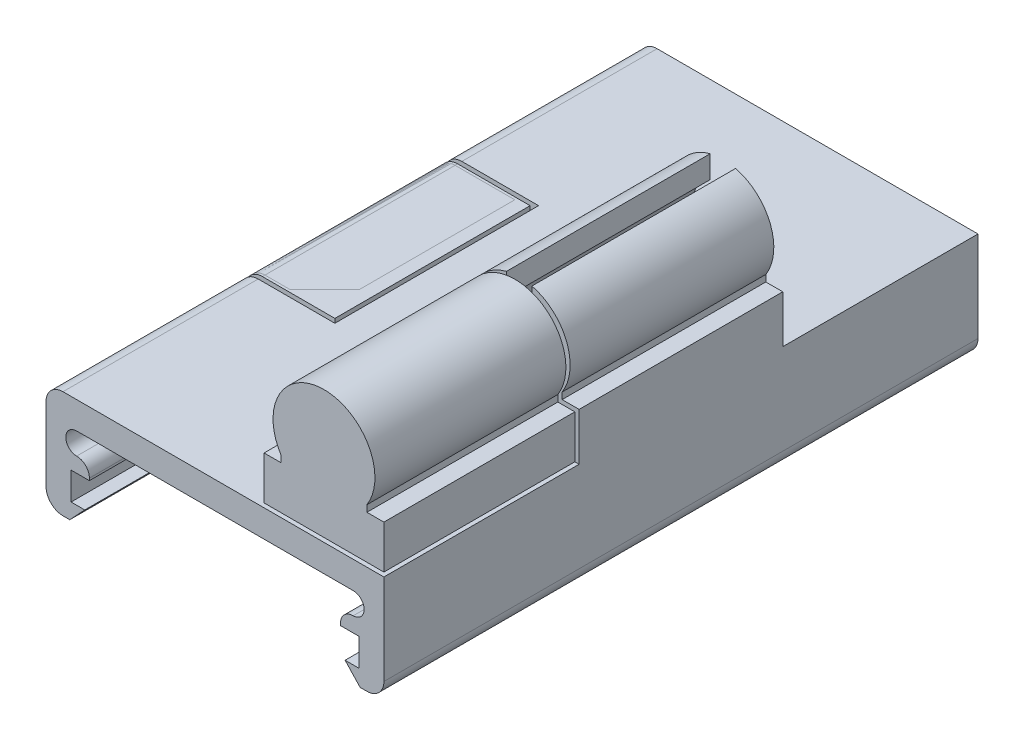
SolidWorks part; units mm, degrees
ref_plane "Front Plane" through (0, 0, 0) normal (0, 0, 1) x (1, 0, 0)
ref_plane "Top Plane" through (0, 0, 0) normal (0, 1, 0) x (1, 0, 0)
ref_plane "Right Plane" through (0, 0, 0) normal (1, 0, 0) x (0, 0, -1)
sketch "Sketch1" plane through (0, 0, 0) normal (0, 0, 1) x (1, 0, 0)
  line L0 (-10, 0.77) -> (7, 0.77) construction
  line L1 (-10, 0.77) -> (-9.1935, 0.77)
  line L2 (-9.1935, 0.77) -> (-10.0783, -0.1732)
  line L3 (-10.0783, -0.1732) -> (-10.478, -0.1732)
  line L4 (-11.478, 0.8268) -> (-11.478, 5.16)
  line L5 (-10.478, 6.16) -> (7.4264, 6.16)
  line L6 (-10, 0.77) -> (-10, 2.4)
  line L7 (-10, 2.4) -> (-8.9215, 2.4)
  line L8 (-8.9215, 2.4) -> (-8.9215, 2.5276)
  line L11 (-9.6715, 4.56) -> (6.6199, 4.56)
  line L12 (-1.5258, -9.4347) -> (-1.5258, -0.4273) construction
  line L13 (-1.5258, 6.16) -> (-1.5258, 4.56) construction
  line L14 (-10, 0.77) -> (-10, 2.4) construction
  line L17 (5.8699, 2.4) -> (5.8699, 2.5276)
  line L18 (6.9484, 2.4) -> (5.8699, 2.4)
  line L19 (6.9484, 0.77) -> (6.9484, 2.4)
  line L20 (8.4264, 0.8268) -> (8.4264, 5.16)
  line L21 (7.0267, -0.1732) -> (7.4264, -0.1732)
  line L22 (6.1419, 0.77) -> (7.0267, -0.1732)
  line L23 (6.9484, 0.77) -> (6.1419, 0.77)
  line L24 (8.4264, 5.16) -> (8.4264, 6.16)
  line L25 (8.4264, 6.16) -> (7.4264, 6.16)
  line L26 (7, 0.77) -> (-10, 0.77) construction
  line L27 (-10, 2.4) -> (7, 2.4) construction
  line L28 (-10, 0.77) -> (7, 0.77) construction
  line L30 (0.73, -0.84) -> (3.37, -0.84) construction
  arc A0 (-10.478, -0.1732) -> (-11.478, 0.8268) centre (-10.478, 0.8268) cw
  arc A1 (-11.478, 5.16) -> (-10.478, 6.16) centre (-10.478, 5.16) cw
  arc A4 (-8.9215, 2.5276) -> (-9.6715, 3.2776) centre (-9.6715, 2.5276) ccw
  arc A5 (5.8699, 2.5276) -> (6.6199, 3.2776) centre (6.6199, 2.5276) cw
  arc A9 (7.4264, -0.1732) -> (8.4264, 0.8268) centre (7.4264, 0.8268) ccw
  arc A12 (-9.6715, 4.56) -> (-9.6715, 3.2776) centre (-9.6715, 3.9188) ccw
  arc A13 (6.6199, 4.56) -> (6.6199, 3.2776) centre (6.6199, 3.9188) cw
  point P48 (6.9742, 3.7616)
  dimension "D2" = 1
  dimension "D8" = 0.75
  dimension "D1" = 0
  dimension "D3" = 7
  dimension "D4" = 1.6
extrude "Boss-Extrude1" add sketch "Sketch1" against normal up to surface (35 mm away)
ref_plane "Plane4" through (0, 0, -17.5) normal (0, 0, 1) x (1, 0, 0)
sketch "Sketch2" plane through (0, 0, -17.5) normal (0, 0, -1) x (-1, 0, 0)
  line L0 (-8.4264, 6.16) -> (10.478, 6.16) construction
  line L1 (-7.4264, 6.16) -> (-2.3705, 6.16)
  line L2 (-2.3705, 9.3446) -> (-2.3705, 6.16)
  line L3 (-7.4264, 9.3446) -> (-7.4264, 6.16)
  line L4 (-8.4264, 0.8268) -> (-8.4264, 6.16) construction
  arc A1 (-2.3705, 9.3446) -> (-7.4264, 9.3446) centre (-4.8984, 10.96) ccw
  circle A2 centre (-4.8984, 10.96) radius 1.75
  dimension "D1" = 3.5
  dimension "D2" = 3
  dimension "D3" = 4.8
  dimension "D4" = 2.528
  dimension "D5" = 1
extrude "Boss-Extrude2" add sketch "Sketch2" along normal mid plane 12
sketch "Sketch3" plane through (0, 6.16, 0) normal (0, 1, 0) x (1, 0, 0)
  line L0 (-7.46, 11.0606) -> (-7.46, 34.5606) construction
  line L1 (-5.96, 23.5) -> (-12.7878, 23.5)
  line L2 (-5.96, 23.5) -> (-5.96, 11.5)
  line L3 (-5.96, 11.5) -> (-12.7878, 11.5)
  line L4 (-12.7878, 23.5) -> (-12.7878, 11.5)
  line L5 (-7.46, 22.5) -> (-10, 22.5) construction
  line L6 (-10, 12.5) -> (-7.46, 12.5) construction
  line L7 (-6.8246, 22.5) -> (-9.3646, 22.5) construction
  line L8 (-9.3646, 12.5) -> (-6.8246, 12.5) construction
  dimension "D1" = 1.5
  dimension "D2" = 1
  dimension "D3" = 1
  dimension "D4" = 1
  dimension "D5" = 6.8278
  dimension "D6" = 1
extrude "Cut-Extrude1" cut sketch "Sketch3" against normal through all
sketch "Sketch4" plane through (0, 0, 0) normal (0, 0, 1) x (1, 0, 0)
  line L0 (8.4264, 6.16) -> (-10.478, 6.16) construction
  line L3 (2.3705, 6.16) -> (7.4264, 6.16)
  line L4 (7.4264, 6.16) -> (7.4264, 9.3446)
  line L5 (2.3705, 9.3446) -> (2.3705, 6.16)
  line L7 (7.4264, 6.41) -> (7.4264, 9.3446)
  line L8 (2.3705, 9.3446) -> (2.3705, 6.41)
  line L9 (2.3705, 6.41) -> (7.4264, 6.41)
  arc A5 (7.4264, 9.3446) -> (2.3705, 9.3446) centre (4.8984, 10.96) ccw
  arc A8 (7.4264, 9.3446) -> (2.3705, 9.3446) centre (4.8984, 10.96) ccw
  dimension "D2" = 0.25
  dimension "D1" = 0
extrude "Boss-Extrude9" add sketch "Sketch4" against normal offset from surface (11.25 mm away) 0.25 separate body up to face at (4.8984, 8.9062, -11.5)
sketch "Sketch6" plane through (0, 0, -23.5) normal (0, 0, 1) x (1, 0, 0)
  line L0 (-6.96, 6.16) -> (-6.96, 4.56)
  line L1 (-5.96, 4.56) -> (-5.96, 6.16) construction
  line L12 (-11.478, 5.16) -> (-11.478, 0.8268)
  line L13 (-10.478, -0.1732) -> (-10.0783, -0.1732)
  line L14 (-10.0783, -0.1732) -> (-9.1935, 0.77)
  line L15 (-9.1935, 0.77) -> (-10, 0.77)
  line L16 (-10, 0.77) -> (-10, 2.4)
  line L17 (-10, 2.4) -> (-8.9215, 2.4)
  line L18 (-8.9215, 2.4) -> (-8.9215, 2.5276)
  line L21 (-9.6715, 4.56) -> (-5.96, 4.56)
  line L22 (-5.96, 4.56) -> (-5.96, 6.16)
  line L23 (-5.96, 6.16) -> (-10.478, 6.16)
  line L24 (-11.478, 5.16) -> (-11.478, 0.8268)
  line L25 (-10.478, -0.1732) -> (-10.0783, -0.1732)
  line L26 (-10.0783, -0.1732) -> (-9.1935, 0.77)
  line L27 (-9.1935, 0.77) -> (-10, 0.77)
  line L28 (-10, 0.77) -> (-10, 2.4)
  line L29 (-10, 2.4) -> (-8.9215, 2.4)
  line L30 (-8.9215, 2.4) -> (-8.9215, 2.5276)
  line L33 (-9.6715, 4.56) -> (-6.96, 4.56)
  line L35 (-6.96, 6.16) -> (-10.478, 6.16)
  arc A4 (-9.6715, 4.56) -> (-9.6715, 3.2776) centre (-9.6715, 3.9188) ccw
  arc A5 (-10.478, 6.16) -> (-11.478, 5.16) centre (-10.478, 5.16) ccw
  arc A6 (-11.478, 0.8268) -> (-10.478, -0.1732) centre (-10.478, 0.8268) ccw
  arc A7 (-8.9215, 2.5276) -> (-9.6715, 3.2776) centre (-9.6715, 2.5276) ccw
  arc A9 (-9.6715, 4.56) -> (-9.6715, 3.2776) centre (-9.6715, 3.9188) ccw
  arc A10 (-10.478, 6.16) -> (-11.478, 5.16) centre (-10.478, 5.16) ccw
  arc A11 (-11.478, 0.8268) -> (-10.478, -0.1732) centre (-10.478, 0.8268) ccw
  arc A12 (-8.9215, 2.5276) -> (-9.6715, 3.2776) centre (-9.6715, 2.5276) ccw
  dimension "D2" = 1
  dimension "D1" = 0
extrude "Boss-Extrude5" add sketch "Sketch6" along normal offset from surface (11.2 mm away) 0.4 from offset 0.4 up to face at (-9.5136, 2.8129, -11.5)
ref_plane "Plane2" through (0, 0, -17.5) normal (0, 0, -1) x (-1, 0, 0)
sketch "Sketch7" plane through (0, 6.16, 0) normal (0, 1, 0) x (1, 0, 0)
  line L0 (7.4264, 23.5) -> (7.4264, 11.5) construction
  line L1 (7.4264, 11.5) -> (8.4264, 11.5)
  line L2 (7.4264, 11.5) -> (7.4264, 23.5)
  line L3 (7.4264, 23.5) -> (8.4264, 23.5)
  line L4 (8.4264, 11.5) -> (8.4264, 23.5)
  line L5 (8.4264, 35) -> (8.4264, 0) construction
  line L6 (2.3705, 23.5) -> (2.3705, 11.5) construction
  line L7 (2.3705, 11.5) -> (1.3705, 11.5)
  line L8 (2.3705, 11.5) -> (2.3705, 23.5)
  line L9 (2.3705, 23.5) -> (1.3705, 23.5)
  line L10 (1.3705, 11.5) -> (1.3705, 23.5)
  line L14 (7.4264, 23.5) -> (2.3705, 23.5) construction
  line L15 (7.4264, 11.5) -> (2.3705, 11.5) construction
extrude "Boss-Extrude6" add sketch "Sketch7" along normal up to surface (2.8 mm away)
ref_plane "Plane3" through (0, 0, -23.25) normal (0, 0, 1) x (1, 0, 0)
sketch "Sketch9" plane through (0, 0, -23.25) normal (0, 0, 1) x (1, 0, 0)
  line L0 (-5.96, 4.56) -> (-5.96, 6.16) construction
  line L12 (-5.96, 6.16) -> (-10.478, 6.16)
  line L13 (-5.96, 4.56) -> (-5.96, 6.16)
  line L14 (-9.6715, 4.56) -> (-5.96, 4.56)
  line L17 (-8.9215, 2.4) -> (-8.9215, 2.5276)
  line L18 (-10, 2.4) -> (-8.9215, 2.4)
  line L19 (-10, 0.77) -> (-10, 2.4)
  line L20 (-9.1935, 0.77) -> (-10, 0.77)
  line L21 (-10.0783, -0.1732) -> (-9.1935, 0.77)
  line L22 (-10.478, -0.1732) -> (-10.0783, -0.1732)
  line L23 (-11.478, 5.16) -> (-11.478, 0.8268)
  line L24 (-6.21, 6.16) -> (-10.478, 6.16)
  line L25 (-6.21, 4.56) -> (-6.21, 6.16)
  line L26 (-9.6715, 4.56) -> (-6.21, 4.56)
  line L29 (-8.9215, 2.4) -> (-8.9215, 2.5276)
  line L30 (-10, 2.4) -> (-8.9215, 2.4)
  line L31 (-10, 0.77) -> (-10, 2.4)
  line L32 (-9.1935, 0.77) -> (-10, 0.77)
  line L33 (-10.0783, -0.1732) -> (-9.1935, 0.77)
  line L34 (-10.478, -0.1732) -> (-10.0783, -0.1732)
  line L35 (-11.478, 5.16) -> (-11.478, 0.8268)
  arc A4 (-9.6715, 4.56) -> (-9.6715, 3.2776) centre (-9.6715, 3.9188) ccw
  arc A5 (-10.478, 6.16) -> (-11.478, 5.16) centre (-10.478, 5.16) ccw
  arc A7 (-9.6715, 4.56) -> (-9.6715, 3.2776) centre (-9.6715, 3.9188) ccw
  arc A8 (-8.9215, 2.5276) -> (-9.6715, 3.2776) centre (-9.6715, 2.5276) ccw
  arc A9 (-11.478, 0.8268) -> (-10.478, -0.1732) centre (-10.478, 0.8268) ccw
  arc A10 (-10.478, 6.16) -> (-11.478, 5.16) centre (-10.478, 5.16) ccw
  arc A13 (-8.9215, 2.5276) -> (-9.6715, 3.2776) centre (-9.6715, 2.5276) ccw
  arc A14 (-11.478, 0.8268) -> (-10.478, -0.1732) centre (-10.478, 0.8268) ccw
  dimension "D2" = 0.25
  dimension "D1" = 0
extrude "Boss-Extrude8" add sketch "Sketch9" along normal offset from surface (11.5 mm away) 0.25 separate body up to face at (-9.5136, 2.8129, -11.5)
sketch "Sketch10" plane through (0, 0, -11.5) normal (0, 0, 1) x (1, 0, 0)
  line L0 (4.8984, 6.6408) -> (4.8984, 22.4484) construction
  line L1 (5.6484, 6.6408) -> (4.1484, 6.6408)
  line L2 (5.6484, 6.6408) -> (5.6484, 22.4484)
  line L3 (5.6484, 22.4484) -> (4.1484, 22.4484)
  line L4 (4.1484, 6.6408) -> (4.1484, 22.4484)
  point P4 (4.8984, 10.96)
  dimension "D1" = 1.5
extrude "Cut-Extrude2" cut sketch "Sketch10" against normal up to surface (12 mm away)
sketch "Sketch11" plane through (0, 0, 0) normal (0, 0, 1) x (1, 0, 0)
  line L4 (8.4264, 8.96) -> (8.4264, 6.16) construction
  line L5 (8.4264, 6.41) -> (1.3705, 6.41)
  line L8 (8.4264, 6.41) -> (8.4264, 8.96)
  line L9 (8.4264, 8.96) -> (1.3705, 8.96)
  line L10 (1.3705, 6.41) -> (1.3705, 8.96)
  line L11 (8.4264, 8.96) -> (7.4264, 8.96) construction
  line L12 (1.3705, 8.96) -> (1.3705, 6.16) construction
  line L13 (2.3705, 6.41) -> (7.4264, 6.41) construction
extrude "Boss-Extrude10" add sketch "Sketch11" against normal up to surface (11.25 mm away) up to face at (4.8984, 9.0312, -11.25)
